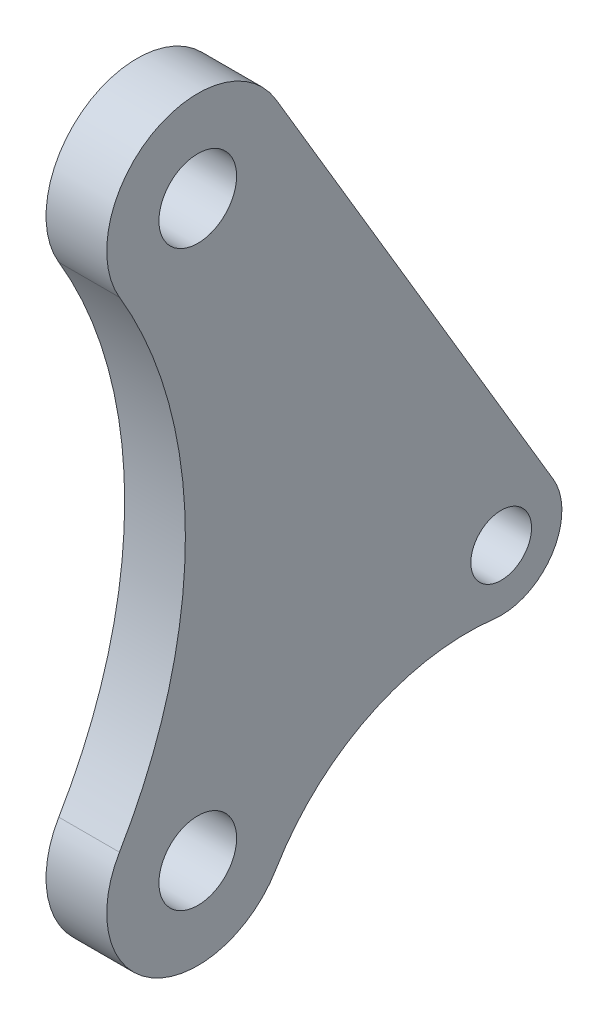
SolidWorks part; units mm, degrees
ref_plane "Front Plane" through (0, 0, 0) normal (0, 0, 1) x (1, 0, 0)
ref_plane "Top Plane" through (0, 0, 0) normal (0, 1, 0) x (1, 0, 0)
ref_plane "Right Plane" through (0, 0, 0) normal (1, 0, 0) x (0, 0, -1)
sketch "Sketch1" plane through (0, 0, 0) normal (1, 0, 0) x (0, 0, -1)
  line L0 (-4.096, 2.4298) -> (4.096, -2.4298) construction
  line L1 (0, 0) -> (15.875, 6.35) construction
  line L2 (15.875, 6.35) -> (0, 30) construction
  line L3 (-4.096, 27.5702) -> (4.096, 32.4298) construction
  line L4 (4.096, 32.4298) -> (18.6057, 7.9699)
  arc A0 (4.096, -2.4298) -> (-4.096, 2.4298) centre (0, 0) cw
  arc A1 (-4.096, 27.5702) -> (4.096, 32.4298) centre (0, 30) cw
  arc A2 (18.6057, 7.9699) -> (15.4994, 3.1973) centre (15.875, 6.35) cw
  arc A3 (15.4994, 3.1973) -> (4.096, -2.4298) centre (14.1204, -8.3762) ccw
  arc A5 (-4.096, 27.5702) -> (-4.096, 2.4298) centre (-25.2865, 15) cw
  dimension "D1" = 30
  dimension "D3" = 9.525
  dimension "D4" = 6.35
  dimension "D2" = 15.875
  dimension "D5" = 6.35
extrude "Boss-Extrude1" add sketch "Sketch1" along normal blind 3.175
sketch "Sketch2" plane through (3.175, 0, 0) normal (1, 0, 0) x (0, 0, -1)
  circle A0 centre (0, 30) radius 2.032
  circle A1 centre (0, 0) radius 2.032
  circle A2 centre (15.875, 6.35) radius 1.5875
  dimension "D1" = 4.064
  dimension "D2" = 3.175
extrude "Cut-Extrude1" cut sketch "Sketch2" against normal through all
